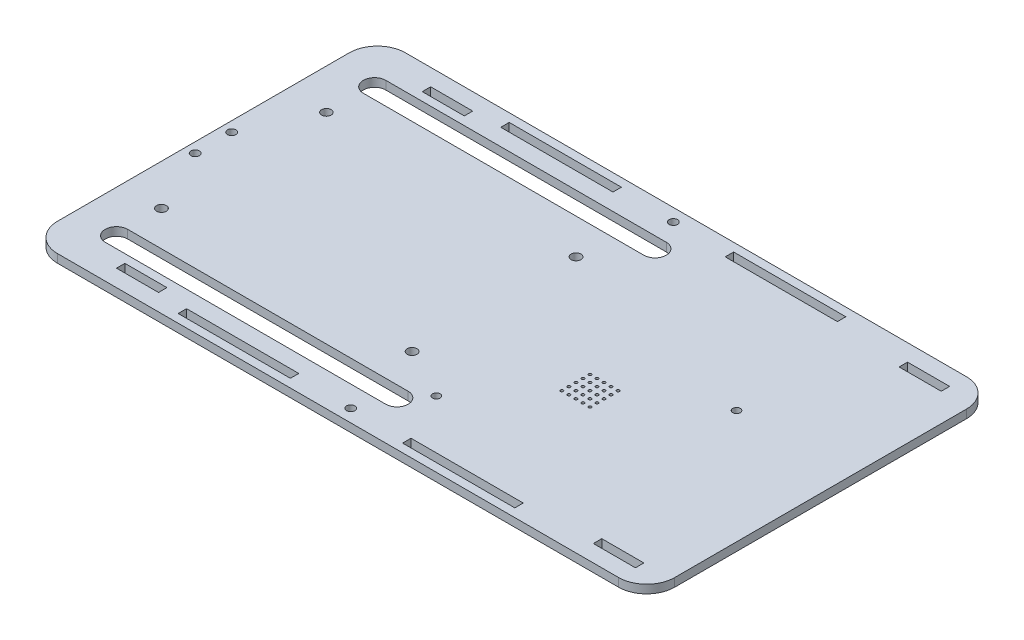
SolidWorks part; units mm, degrees
ref_plane "Front Plane" through (0, 0, 0) normal (0, 0, 1) x (1, 0, 0)
ref_plane "Top Plane" through (0, 0, 0) normal (0, 1, 0) x (1, 0, 0)
ref_plane "Right Plane" through (0, 0, 0) normal (1, 0, 0) x (0, 0, -1)
sketch "Sketch1" plane through (0, 0, 0) normal (0, 1, 0) x (1, 0, 0)
  line L0 (0, 62) -> (0, -68) construction
  line L1 (-100, -62) -> (100, -62)
  line L2 (-110, -52) -> (-110, 52)
  line L3 (-100, 62) -> (100, 62)
  line L4 (110, -52) -> (110, 52)
  line L5 (-110, -62) -> (110, 62) construction
  line L6 (-110, 62) -> (110, -62) construction
  line L7 (-110, 0) -> (110, 0) construction
  arc A0 (110, 52) -> (100, 62) centre (100, 52) ccw
  arc A1 (100, -62) -> (110, -52) centre (100, -52) ccw
  arc A2 (-110, -52) -> (-100, -62) centre (-100, -52) ccw
  arc A3 (-100, 62) -> (-110, 52) centre (-100, 52) ccw
  circle A4 centre (69.4726, 10.5717) radius 1.35
  circle A5 centre (11.4726, -38.4283) radius 1.35
  point P0 (0, 0)
  dimension "D3" = 10
  dimension "D4" = 10
  dimension "D5" = 10
  dimension "D6" = 10
  dimension "D1" = 124
  dimension "D2" = 220
extrude "Boss-Extrude1" add sketch "Sketch1" along normal blind 3
sketch "Sketch4" plane through (0, 3, 0) normal (0, 1, 0) x (1, 0, 0)
  line L0 (0, 62) -> (0, -62) construction
  line L1 (-60, -59) -> (-20, -59)
  line L2 (-60, -59) -> (-60, -56)
  line L3 (-60, -56) -> (-20, -56)
  line L4 (-20, -59) -> (-20, -56)
  line L9 (100, 62) -> (-100, 62) construction
  line L10 (-100, -62) -> (100, -62) construction
  line L11 (-110, 0) -> (110, 0) construction
  line L12 (-110, 52) -> (-110, -52) construction
  line L13 (110, -52) -> (110, 52) construction
  line L14 (20, -59) -> (20, -56)
  line L15 (60, -59) -> (20, -59)
  line L16 (60, -59) -> (60, -56)
  line L17 (60, -56) -> (20, -56)
  line L18 (-60, 56) -> (-20, 56)
  line L19 (-20, 59) -> (-20, 56)
  line L20 (-60, 59) -> (-20, 59)
  line L21 (-60, 59) -> (-60, 56)
  line L22 (60, 59) -> (20, 59)
  line L23 (60, 59) -> (60, 56)
  line L24 (60, 56) -> (20, 56)
  line L25 (20, 59) -> (20, 56)
  line L26 (0, -62) -> (0, -57.5) construction
  circle A0 centre (0, -57.5) radius 1.5
  circle A1 centre (0, 57.5) radius 1.5
  dimension "D6" = 3
  dimension "D1" = 3
  dimension "D2" = 3
  dimension "D3" = 20
  dimension "D4" = 40
  dimension "D5" = 4.5
extrude "Cut-Extrude1" cut sketch "Sketch4" against normal blind 3
sketch "Sketch5" plane through (0, 3, 0) normal (0, 1, 0) x (1, 0, 0)
  circle A0 centre (-95.6818, 29.5113) radius 1.7
  circle A1 centre (-95.4255, -29.5285) radius 1.75
  circle A2 centre (-6.5757, -29.029) radius 1.75
  circle A3 centre (-6.5817, 29.401) radius 1.75
extrude "Cut-Extrude2" cut sketch "Sketch5" against normal blind 3
sketch "Sketch6" plane through (0, 3, 0) normal (0, 1, 0) x (1, 0, 0)
  line L4 (44.7226, -1.9283) -> (29.7226, -1.9283) construction
  line L6 (29.7226, -1.9283) -> (29.7226, -16.9283) construction
  circle A0 centre (32.2226, -4.4283) radius 0.5
  circle A1 centre (34.7226, -4.4283) radius 0.5
  circle A2 centre (37.2226, -4.4283) radius 0.5
  circle A3 centre (39.7226, -4.4283) radius 0.5
  circle A4 centre (-29.9846, 187.3222) radius 0.5
  circle A5 centre (42.2226, -4.4283) radius 0.5
  circle A6 centre (32.2226, -6.9283) radius 0.5
  circle A7 centre (34.7226, -6.9283) radius 0.5
  circle A8 centre (37.2226, -6.9283) radius 0.5
  circle A9 centre (39.7226, -6.9283) radius 0.5
  circle A10 centre (42.2226, -6.9283) radius 0.5
  circle A11 centre (32.2226, -9.4283) radius 0.5
  circle A12 centre (34.7226, -9.4283) radius 0.5
  circle A13 centre (37.2226, -9.4283) radius 0.5
  circle A14 centre (39.7226, -9.4283) radius 0.5
  circle A15 centre (42.2226, -9.4283) radius 0.5
  circle A16 centre (32.2226, -11.9283) radius 0.5
  circle A17 centre (34.7226, -11.9283) radius 0.5
  circle A18 centre (37.2226, -11.9283) radius 0.5
  circle A19 centre (39.7226, -11.9283) radius 0.5
  circle A20 centre (42.2226, -11.9283) radius 0.5
  circle A21 centre (32.2226, -14.4283) radius 0.5
  circle A22 centre (34.7226, -14.4283) radius 0.5
  circle A23 centre (37.2226, -14.4283) radius 0.5
  circle A24 centre (39.7226, -14.4283) radius 0.5
  circle A25 centre (42.2226, -14.4283) radius 0.5
  dimension "D1" = 1
  dimension "D2" = 1
  dimension "D3" = 1
  dimension "D4" = 1
  dimension "D10" = 1
  dimension "D5" = 2.5
  dimension "D6" = 2.5
  dimension "D7" = 2.5
  dimension "D8" = 2.5
  dimension "D9" = 2.5
  dimension "D11" = 2.5
  dimension "D12" = 2.5
  dimension "D13" = 2.5
  dimension "D14" = 2.5
  dimension "D15" = 2.5
  dimension "D16" = 2.5
  dimension "D17" = 2.5
  dimension "D18" = 2.5
  dimension "D19" = 2.5
  dimension "D20" = 2.5
  dimension "D21" = 2.5
  dimension "D22" = 2.5
  dimension "D23" = 2.5
  dimension "D24" = 2.5
  dimension "D25" = 2.5
  dimension "D26" = 2.5
  dimension "D27" = 2.5
  dimension "D28" = 2.5
  dimension "D29" = 2.5
  dimension "D30" = 2.5
  dimension "D31" = 2.5
  dimension "D32" = 2.5
  dimension "D33" = 2.5
  dimension "D34" = 2.5
  dimension "D35" = 2.5
extrude "Cut-Extrude3" cut sketch "Sketch6" against normal blind 3
sketch "Sketch7" plane through (0, 3, 0) normal (0, 1, 0) x (1, 0, 0)
  line L0 (-110, 12.5) -> (-112.5063, 12.5) construction
  line L1 (-112.5063, -12.5) -> (-110, -12.5) construction
  circle A0 centre (-106.4373, 6.5) radius 1.5
  circle A1 centre (-106.4373, -6.5) radius 1.5
  dimension "D1" = 3
  dimension "D2" = 3
  dimension "D3" = 6
  dimension "D4" = 6
extrude "Cut-Extrude4" cut sketch "Sketch7" against normal blind 3
sketch "Sketch8" plane through (0, 3, 0) normal (0, 1, 0) x (1, 0, 0)
  line L0 (-95, 46) -> (5, 46) construction
  line L1 (-95, 50) -> (5, 50)
  line L2 (-95, 42) -> (5, 42)
  line L3 (-110, 52) -> (-110, -52) construction
  line L4 (-35, 56) -> (45, 56) construction
  line L5 (-95, -46) -> (5, -46) construction
  line L6 (-95, -42) -> (5, -42)
  line L7 (-95, -50) -> (5, -50)
  line L9 (-35, -56) -> (45, -56) construction
  arc A0 (-95, 50) -> (-95, 42) centre (-95, 46) ccw
  arc A1 (5, 42) -> (5, 50) centre (5, 46) ccw
  arc A2 (-95, -42) -> (-95, -50) centre (-95, -46) ccw
  arc A3 (5, -50) -> (5, -42) centre (5, -46) ccw
  point P2 (-45, 46)
  point P13 (-45, -46)
  dimension "D1" = 8
  dimension "D2" = 100
  dimension "D3" = 65
  dimension "D4" = 10
  dimension "D5" = 8
  dimension "D6" = 10
  dimension "D7" = 65
  dimension "D8" = 100
extrude "Cut-Extrude5" cut sketch "Sketch8" against normal blind 3
sketch "Sketch9" plane through (0, 3, 0) normal (0, 1, 0) x (1, 0, 0)
  line L1 (-85, -56) -> (-70, -56)
  line L2 (-85, -56) -> (-85, -53)
  line L3 (-85, -53) -> (-70, -53)
  line L4 (-70, -56) -> (-70, -53)
  line L5 (-70, 53) -> (-85, 53)
  line L6 (-70, 53) -> (-70, 56)
  line L7 (-70, 56) -> (-85, 56)
  line L8 (-85, 53) -> (-85, 56)
  line L9 (85, 53) -> (100, 53)
  line L10 (85, 53) -> (85, 56)
  line L11 (85, 56) -> (100, 56)
  line L12 (100, 53) -> (100, 56)
  line L13 (85, -53) -> (100, -53)
  line L14 (85, -53) -> (85, -56)
  line L15 (85, -56) -> (100, -56)
  line L16 (100, -53) -> (100, -56)
extrude "Cut-Extrude6" cut sketch "Sketch9" against normal blind 3
